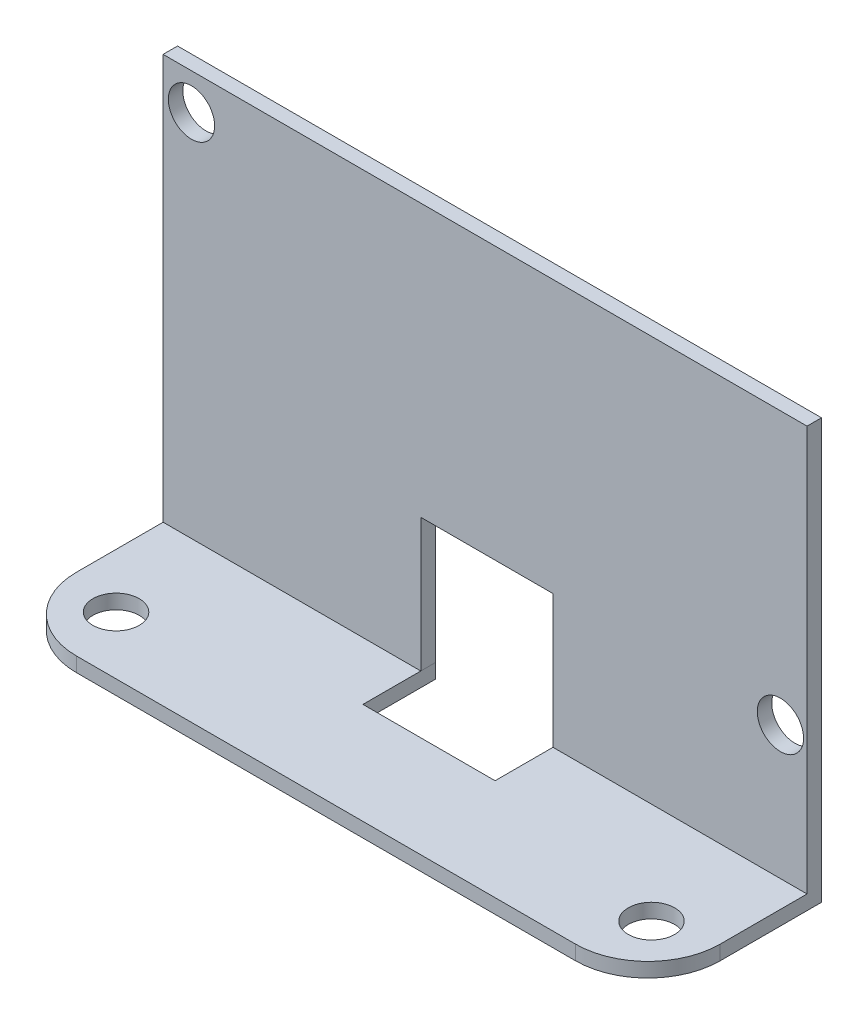
SolidWorks part; units mm, degrees
ref_plane "Front Plane" through (0, 0, 0) normal (0, 0, 1) x (1, 0, 0)
ref_plane "Top Plane" through (0, 0, 0) normal (0, 1, 0) x (1, 0, 0)
ref_plane "Right Plane" through (0, 0, 0) normal (1, 0, 0) x (0, 0, -1)
sketch "Sketch1" plane through (0, 0, 0) normal (0, 0, 1) x (1, 0, 0)
  line L1 (-18.1572, 6.6101) -> (26.3428, 6.6101)
  line L2 (-18.1572, 6.6101) -> (-18.1572, -22.3899)
  line L3 (-18.1572, -22.3899) -> (26.3428, -22.3899)
  line L4 (26.3428, 6.6101) -> (26.3428, -22.3899)
  dimension "D1" = 29
  dimension "D2" = 44.5
extrude "Boss-Extrude1" add sketch "Sketch1" along normal blind 12
sketch "Sketch2" plane through (-18.1572, 0, 0) normal (-1, 0, 0) x (0, 0, 1)
  line L0 (12, 6.6101) -> (0, 6.6101) construction
  line L1 (0, -22.3899) -> (1, -22.3899)
  line L2 (0, -22.3899) -> (0, 6.6101)
  line L3 (0, 6.6101) -> (1, 6.6101)
  line L4 (1, -22.3899) -> (1, 6.6101)
  line L5 (12, -22.3899) -> (-0.0034, -22.3899)
  line L6 (12, -22.3899) -> (12, -21.3899)
  line L7 (12, -21.3899) -> (-0.0034, -21.3899)
  line L8 (-0.0034, -22.3899) -> (-0.0034, -21.3899)
  line L9 (0, 6.6101) -> (0, -22.3899) construction
  line L10 (12, -22.3899) -> (0, -22.3899) construction
  line L11 (12, 6.6101) -> (12, -22.3899) construction
  line M3 (12, -22.3899) -> (12, 6.6101)
  line M4 (12, 6.6101) -> (0, 6.6101)
  dimension "D1" = 1
  dimension "D2" = 1
extrude "Cut-Extrude1" cut sketch "Sketch2" against normal through all contours L7 L4 M3 M4
sketch "Sketch3" plane through (0, 0, 1) normal (0, 0, 1) x (1, 0, 0)
  line L2 (26.3428, -21.3899) -> (-18.1572, -21.3899) construction
  line L3 (8.7859, -12.1899) -> (-0.348, -12.1899)
  line L4 (8.7859, -12.1899) -> (8.7859, -21.3899)
  line L5 (8.7859, -21.3899) -> (-0.348, -21.3899)
  line L6 (-0.348, -12.1899) -> (-0.348, -21.3899)
  line L7 (8.7859, -12.1899) -> (-0.348, -21.3899) construction
  line L8 (8.7859, -21.3899) -> (-0.348, -12.1899) construction
  circle A0 centre (-16.196, 4.1101) radius 1.6
  circle A1 centre (24.504, -12.1899) radius 1.6
  point P12 (4.2189, -16.7899)
  dimension "D1" = 3.2
  dimension "D2" = 9.2
  dimension "D3" = 9.1339
extrude "Cut-Extrude2" cut sketch "Sketch3" against normal blind 16.77
sketch "Sketch4" plane through (0, -21.3899, 0) normal (0, 1, 0) x (1, 0, 0)
  line L0 (26.3428, -12) -> (26.3428, -1) construction
  line L1 (26.3428, -12) -> (-18.1572, -12) construction
  circle A0 centre (-14.4072, -8) radius 1.6
  circle A1 centre (22.5928, -8) radius 1.6
  dimension "D1" = 3.2
  dimension "D6" = 3.2
  dimension "D2" = 37
  dimension "D3" = 3.75
  dimension "D4" = 4
  dimension "D5" = 4
extrude "Cut-Extrude4" cut sketch "Sketch4" against normal blind 16.77
fillet "Fillet1" radius 5 1 edges at (-18.1572, -21.8899, 12)
fillet "Fillet2" radius 5 1 edges at (26.3428, -21.8899, 12)
sketch "Sketch11" plane through (0, 0, 0) normal (0, 0, -1) x (-1, 0, 0)
  line L1 (-8.7859, -21.3899) -> (0.3479, -21.3899)
  line L2 (-8.7859, -21.3899) -> (-8.7859, -23.3899)
  line L3 (-8.7859, -23.3899) -> (0.3479, -23.3899)
  line L4 (0.3479, -21.3899) -> (0.3479, -23.3899)
  line L5 (-8.7859, -21.3899) -> (0.3479, -23.3899) construction
  line L6 (-8.7859, -23.3899) -> (0.3479, -21.3899) construction
  point P4 (-4.219, -22.3899)
  dimension "D1" = 2
  dimension "D2" = 9.1338
extrude "Cut-Extrude7" cut sketch "Sketch11" against normal blind 5
